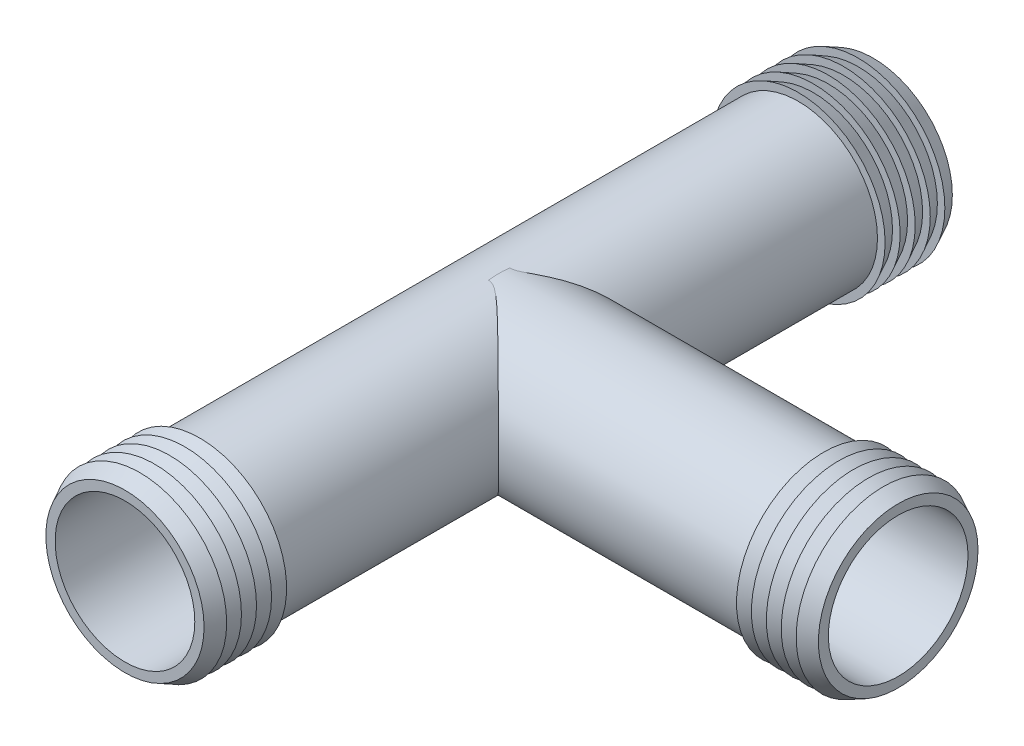
SolidWorks part; units mm, degrees
ref_plane "Front Plane" through (0, 0, 0) normal (0, 0, 1) x (1, 0, 0)
ref_plane "Top Plane" through (0, 0, 0) normal (0, 1, 0) x (1, 0, 0)
ref_plane "Right Plane" through (0, 0, 0) normal (1, 0, 0) x (0, 0, -1)
sketch "Sketch1" plane through (0, 0, 0) normal (0, 0, 1) x (1, 0, 0)
  circle A0 centre (0, 0) radius 15.8585
  circle A1 centre (0, 0) radius 14
  dimension "D1" = 28
extrude "Boss-Extrude1" add sketch "Sketch1" along normal blind 75 and the other way blind 75
sketch "Sketch2" plane through (0, 0, 0) normal (1, 0, 0) x (0, 0, -1)
  line L0 (75, 15.8585) -> (72, 15.8585)
  line L1 (75, 15.8585) -> (-75, 15.8585) construction
  line L2 (72, 15.8585) -> (72, 17.3585)
  line L3 (72, 17.3585) -> (75, 15.8585)
  line L4 (0, 0) -> (93.533, 0) construction
  dimension "D1" = 3
  dimension "D2" = 1.5
revolve "Revolve1" add sketch "Sketch2" angle 360 about L4
sketch "Sketch3" plane through (0, 0, 0) normal (1, 0, 0) x (0, 0, -1)
  line L0 (72, 15.8585) -> (69.0405, 15.8585)
  line L2 (69.0405, 15.8585) -> (69.0405, 17.3932)
  line L3 (69.0405, 17.3932) -> (72, 15.8585)
  line L4 (0, 0) -> (85.1914, 0) construction
revolve "Revolve2" add sketch "Sketch3" angle 360 about L4
sketch "Sketch4" plane through (0, 0, 0) normal (1, 0, 0) x (0, 0, -1)
  line L0 (69.0405, 15.8585) -> (66.0233, 15.8585)
  line L1 (66.0233, 15.8585) -> (66.0233, 17.3932)
  line L2 (66.0233, 17.3932) -> (69.0405, 15.8585)
  line L3 (0, 0) -> (85.9013, 0) construction
revolve "Revolve3" add sketch "Sketch4" angle 360 about L3
sketch "Sketch5" plane through (0, 0, 0) normal (1, 0, 0) x (0, 0, -1)
  line L0 (66.0233, 15.8585) -> (63.0061, 15.8585)
  line L1 (63.0061, 15.8585) -> (63.0061, 17.3932)
  line L2 (63.0061, 17.3932) -> (66.0233, 15.8585)
  line L3 (0, 0) -> (81.8192, 0) construction
revolve "Revolve4" add sketch "Sketch5" angle 360 about L3
sketch "Sketch6" plane through (0, 0, 0) normal (1, 0, 0) x (0, 0, -1)
  line L0 (63.0061, 15.8585) -> (59.9889, 15.8585)
  line L1 (59.9889, 15.8585) -> (59.9889, 17.3932)
  line L2 (59.9889, 17.3932) -> (63.0061, 15.8585)
  line L3 (0, 0) -> (80.5768, 0) construction
revolve "Revolve5" add sketch "Sketch6" angle 360 about L3
sketch "Sketch7" plane through (0, 0, 0) normal (1, 0, 0) x (0, 0, -1)
  line L0 (-75, 15.8585) -> (-72, 15.8585)
  line L1 (59.9889, 15.8585) -> (-75, 15.8585) construction
  line L2 (-72, 15.8585) -> (-72, 17.3932)
  line L3 (-72, 17.3932) -> (-75, 15.8585)
  line L4 (0, 0) -> (88.5635, 0) construction
  dimension "D1" = 3
revolve "Revolve6" add sketch "Sketch7" angle 360 about L4
sketch "Sketch8" plane through (0, 0, 0) normal (1, 0, 0) x (0, 0, -1)
  line L0 (-72, 15.8585) -> (-69.0405, 15.8585)
  line L1 (-69.0405, 15.8585) -> (-69.0405, 17.3932)
  line L2 (-69.0405, 17.3932) -> (-72, 15.8585)
  line L3 (0, 0) -> (82.3517, 0) construction
revolve "Revolve7" add sketch "Sketch8" angle 360 about L3
sketch "Sketch9" plane through (0, 0, 0) normal (1, 0, 0) x (0, 0, -1)
  line L0 (-69.0405, 15.8585) -> (-66.0233, 15.8585)
  line L1 (59.9889, 15.8585) -> (-69.0405, 15.8585) construction
  line L2 (-66.0233, 15.8585) -> (-66.0233, 17.3932)
  line L3 (-66.0233, 17.3932) -> (-69.0405, 15.8585)
  line L4 (0, 0) -> (61.0538, 0) construction
revolve "Revolve8" add sketch "Sketch9" angle 360 about L4
sketch "Sketch10" plane through (0, 0, 0) normal (1, 0, 0) x (0, 0, -1)
  line L0 (-66.0233, 15.8585) -> (-63.0061, 15.8585)
  line L1 (59.9889, 15.8585) -> (-66.0233, 15.8585) construction
  line L2 (-63.0061, 15.8585) -> (-63.0061, 17.3932)
  line L3 (-63.0061, 17.3932) -> (-66.0233, 15.8585)
  line L4 (0, 0) -> (28.2196, 0) construction
revolve "Revolve9" add sketch "Sketch10" angle 360 about L4
sketch "Sketch11" plane through (0, 0, 0) normal (1, 0, 0) x (0, 0, -1)
  line L0 (-63.0061, 15.8585) -> (-59.9889, 15.8585)
  line L1 (59.9889, 15.8585) -> (-63.0061, 15.8585) construction
  line L2 (-59.9889, 15.8585) -> (-59.9889, 17.3932)
  line L3 (-59.9889, 17.3932) -> (-63.0061, 15.8585)
  line L4 (0, 0) -> (-13.3112, 0) construction
revolve "Revolve10" add sketch "Sketch11" angle 360 about L4
sketch "Sketch12" plane through (0, 0, 0) normal (1, 0, 0) x (0, 0, -1)
  circle A0 centre (0, 0) radius 14
  circle A1 centre (0, 0) radius 16
  dimension "D1" = 28
  dimension "D2" = 32
extrude "Boss-Extrude2" add sketch "Sketch12" along normal blind 80
sketch "Sketch13" plane through (0, 0, 0) normal (1, 0, 0) x (0, 0, -1)
  circle A0 centre (0, 0) radius 14
extrude "Cut-Extrude1" cut sketch "Sketch13" along normal blind 81
sketch "Sketch15" plane through (0, 0, 0) normal (0, 0, 1) x (1, 0, 0)
  circle A0 centre (0, 0) radius 14
extrude "Cut-Extrude2" cut sketch "Sketch15" against normal blind 95 and the other way blind 90
sketch "Sketch16" plane through (0, 0, 0) normal (0, 0, 1) x (1, 0, 0)
  line L0 (80, 16) -> (77.0134, 16)
  line L1 (80, 16) -> (0, 16) construction
  line L2 (77.0134, 16) -> (77.0134, 17.472)
  line L3 (77.0134, 17.472) -> (80, 16)
  line L4 (0, 0) -> (-22.9909, 0) construction
revolve "Revolve11" add sketch "Sketch16" angle 360 about L4
sketch "Sketch17" plane through (0, 0, 0) normal (0, 0, 1) x (1, 0, 0)
  line L0 (77.0134, 16) -> (74.0247, 16)
  line L1 (74.0247, 16) -> (74.0247, 17.472)
  line L2 (74.0247, 17.472) -> (77.0134, 16)
  line L3 (0, 0) -> (-19.3126, 0) construction
revolve "Revolve12" add sketch "Sketch17" angle 360 about L3
sketch "Sketch18" plane through (0, 0, 0) normal (0, 0, 1) x (1, 0, 0)
  line L0 (74.0247, 16) -> (71.0361, 16)
  line L1 (74.0247, 16) -> (0, 16) construction
  line L2 (71.0361, 16) -> (71.0361, 17.472)
  line L3 (71.0361, 17.472) -> (74.0247, 16)
  line L4 (0, 0) -> (-20.577, 0) construction
revolve "Revolve13" add sketch "Sketch18" angle 360 about L4
sketch "Sketch19" plane through (0, 0, 0) normal (0, 0, 1) x (1, 0, 0)
  line L0 (71.0361, 16) -> (68.0475, 16)
  line L2 (68.0475, 16) -> (68.0475, 17.472)
  line L3 (68.0475, 17.472) -> (71.0361, 16)
  line L4 (0, 0) -> (-19.6574, 0) construction
revolve "Revolve14" add sketch "Sketch19" angle 360 about L4
sketch "Sketch20" plane through (0, 0, 0) normal (0, 0, 1) x (1, 0, 0)
  line L0 (68.0475, 16) -> (65.0588, 16)
  line L1 (65.0588, 16) -> (65.0588, 17.472)
  line L2 (65.0588, 17.472) -> (68.0475, 16)
  line L3 (0, 0) -> (-24.3703, 0) construction
revolve "Revolve15" add sketch "Sketch20" angle 360 about L3
